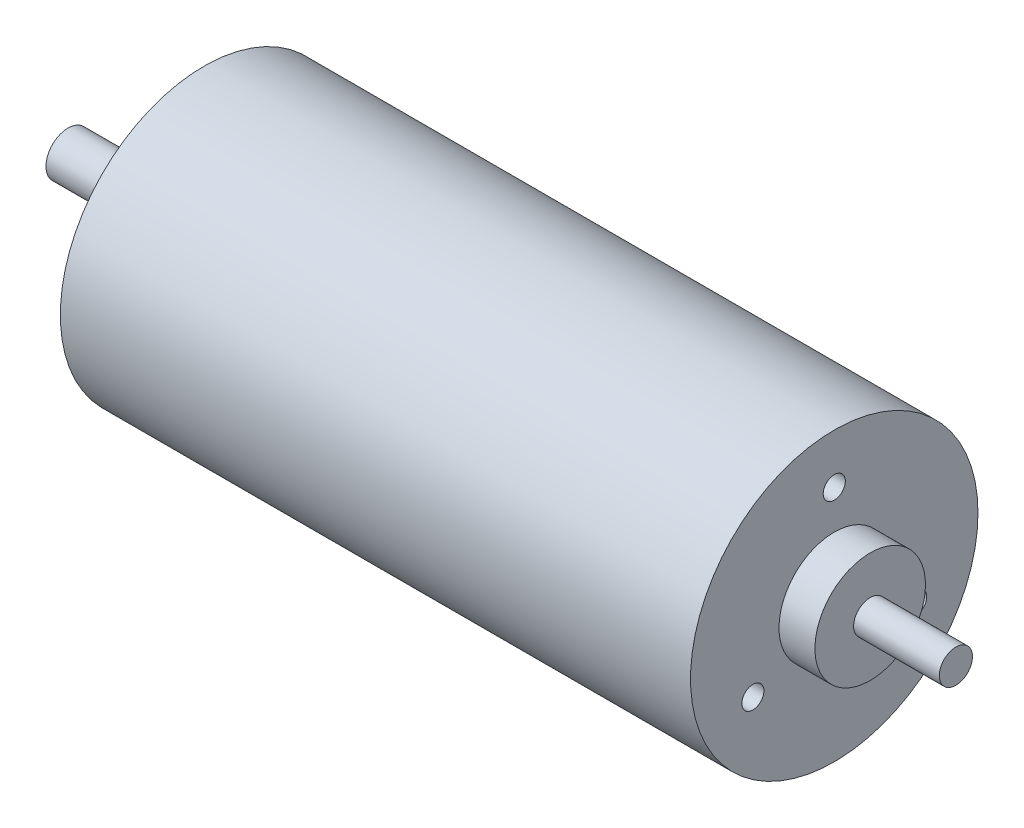
SolidWorks part; units mm, degrees
ref_plane "Płaszczyzna przednia" through (0, 0, 0) normal (0, 0, 1) x (1, 0, 0)
ref_plane "Płaszczyzna górna" through (0, 0, 0) normal (0, 1, 0) x (1, 0, 0)
ref_plane "Płaszczyzna prawa" through (0, 0, 0) normal (1, 0, 0) x (0, 0, -1)
sketch "Szkic1" plane through (0, 0, 0) normal (0, 0, 1) x (1, 0, 0)
  line L0 (0, 0) -> (-50000, 0) construction
  line L1 (0, 0) -> (0, 2)
  line L2 (0, 2) -> (11.2, 2)
  line L3 (11.2, 2) -> (11.2, 5)
  line L5 (69.3, 13) -> (69.3, 5)
  line L6 (69.3, 5) -> (72.55, 5)
  line L7 (72.55, 5) -> (72.55, 1.5)
  line L8 (72.55, 1.5) -> (80.3, 1.5)
  line L9 (80.3, 1.5) -> (80.3, 0)
  line L10 (80.3, 0) -> (0, 0)
  line L11 (11.2, 5) -> (12.3, 5)
  line L12 (12.3, 5) -> (12.3, 13)
  line L13 (12.3, 13) -> (69.3, 13)
  dimension "D1" = 4
  dimension "D2" = 12.3
  dimension "D3" = 1.1
  dimension "D4" = 10
  dimension "D5" = 57
  dimension "D6" = 26
  dimension "D7" = 10
  dimension "D8" = 3
  dimension "D9" = 3.25
  dimension "D10" = 11
revolve "Obrót1" add sketch "Szkic1" angle 360 about L0
sketch "Szkic2" plane through (69.3, 0, 0) normal (1, 0, 0) x (0, 0, -1)
  circle A0 centre (0, 8.5) radius 1
  circle A1 centre (0, 0) radius 8.5 construction
  circle A2 centre (7.3612, -4.25) radius 1
  circle A3 centre (-7.3612, -4.25) radius 1
  point P12 (0, 0)
  dimension "D1" = 2
  dimension "D2" = 17
  dimension "D3" = 3
extrude "Wytnij-wyciągnięcie1" cut sketch "Szkic2" against normal blind 2.9
